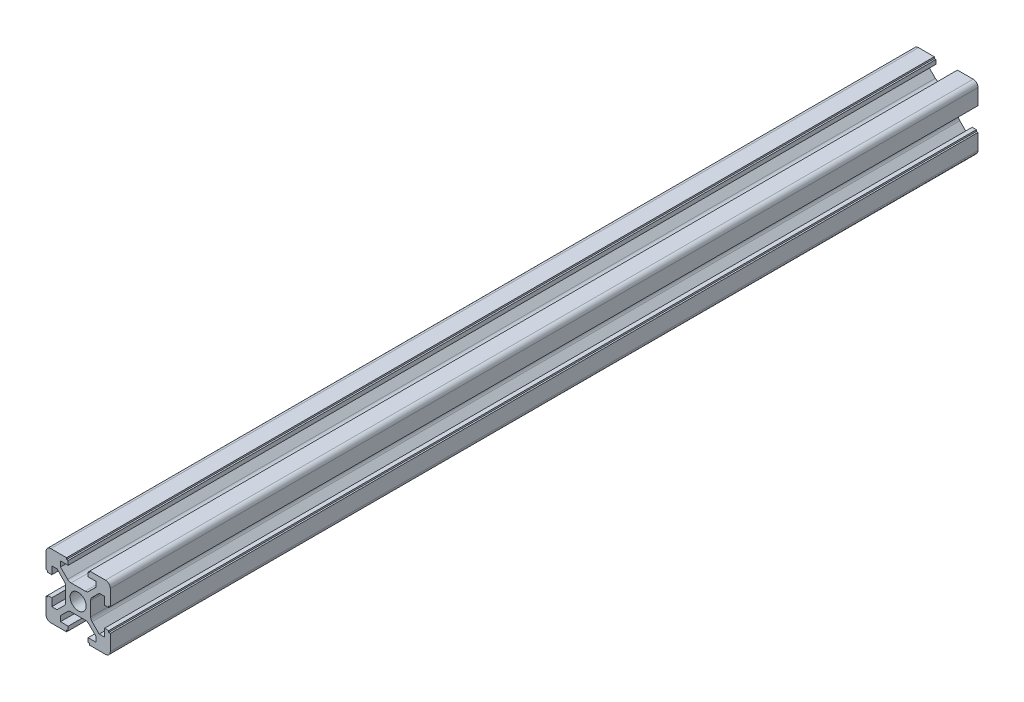
SolidWorks part; units mm, degrees
material "6061 合金"
ref_plane "前视基准面" through (0, 0, 0) normal (0, 0, 1) x (1, 0, 0)
ref_plane "上视基准面" through (0, 0, 0) normal (0, 1, 0) x (1, 0, 0)
ref_plane "右视基准面" through (0, 0, 0) normal (1, 0, 0) x (0, 0, -1)
sketch "草图1" plane through (0, 0, 0) normal (0, 0, 1) x (1, 0, 0)
  line L0 (-6.5607, 5.5) -> (-4.3393, 3.2787)
  line L1 (-3.9, 2.218) -> (-3.9, -2.218)
  line L2 (-4.3393, -3.2787) -> (-6.5607, -5.5)
  line L3 (-6.5607, -5.5) -> (-8.2, -5.5)
  line L4 (-8.2, -5.5) -> (-8.2, -3.1)
  line L5 (-8.2, -3.1) -> (-9.5, -3.1)
  line L6 (-9.5, -3.1) -> (-9.5, -3.6)
  line L7 (-9.5, -3.6) -> (-10, -3.6)
  line L8 (-10, -3.6) -> (-10, -8.5)
  line L9 (-6.5607, 5.5) -> (-8.2, 5.5)
  line L10 (-8.2, 5.5) -> (-8.2, 3.1)
  line L11 (-8.2, 3.1) -> (-9.5, 3.1)
  line L12 (-9.5, 3.1) -> (-9.5, 3.6)
  line L13 (-9.5, 3.6) -> (-10, 3.6)
  line L14 (-10, 3.6) -> (-10, 8.5)
  line L15 (5.5, 6.5607) -> (3.2787, 4.3393)
  line L16 (2.218, 3.9) -> (-2.218, 3.9)
  line L17 (-3.2787, 4.3393) -> (-5.5, 6.5607)
  line L18 (-5.5, 6.5607) -> (-5.5, 8.2)
  line L19 (-5.5, 8.2) -> (-3.1, 8.2)
  line L20 (-3.1, 8.2) -> (-3.1, 9.5)
  line L21 (-3.1, 9.5) -> (-3.6, 9.5)
  line L22 (-3.6, 9.5) -> (-3.6, 10)
  line L23 (-3.6, 10) -> (-8.5, 10)
  line L24 (5.5, 6.5607) -> (5.5, 8.2)
  line L25 (5.5, 8.2) -> (3.1, 8.2)
  line L26 (3.1, 8.2) -> (3.1, 9.5)
  line L27 (3.1, 9.5) -> (3.6, 9.5)
  line L28 (3.6, 9.5) -> (3.6, 10)
  line L29 (3.6, 10) -> (8.5, 10)
  line L30 (6.5607, -5.5) -> (4.3393, -3.2787)
  line L31 (3.9, -2.218) -> (3.9, 2.218)
  line L32 (4.3393, 3.2787) -> (6.5607, 5.5)
  line L33 (6.5607, 5.5) -> (8.2, 5.5)
  line L34 (8.2, 5.5) -> (8.2, 3.1)
  line L35 (8.2, 3.1) -> (9.5, 3.1)
  line L36 (9.5, 3.1) -> (9.5, 3.6)
  line L37 (9.5, 3.6) -> (10, 3.6)
  line L38 (10, 3.6) -> (10, 8.5)
  line L39 (6.5607, -5.5) -> (8.2, -5.5)
  line L40 (8.2, -5.5) -> (8.2, -3.1)
  line L41 (8.2, -3.1) -> (9.5, -3.1)
  line L42 (9.5, -3.1) -> (9.5, -3.6)
  line L43 (9.5, -3.6) -> (10, -3.6)
  line L44 (10, -3.6) -> (10, -8.5)
  line L45 (-5.5, -6.5607) -> (-3.2787, -4.3393)
  line L46 (-2.218, -3.9) -> (2.218, -3.9)
  line L47 (3.2787, -4.3393) -> (5.5, -6.5607)
  line L48 (5.5, -6.5607) -> (5.5, -8.2)
  line L49 (5.5, -8.2) -> (3.1, -8.2)
  line L50 (3.1, -8.2) -> (3.1, -9.5)
  line L51 (3.1, -9.5) -> (3.6, -9.5)
  line L52 (3.6, -9.5) -> (3.6, -10)
  line L53 (3.6, -10) -> (8.5, -10)
  line L54 (-5.5, -6.5607) -> (-5.5, -8.2)
  line L55 (-5.5, -8.2) -> (-3.1, -8.2)
  line L56 (-3.1, -8.2) -> (-3.1, -9.5)
  line L57 (-3.1, -9.5) -> (-3.6, -9.5)
  line L58 (-3.6, -9.5) -> (-3.6, -10)
  line L59 (-3.6, -10) -> (-8.5, -10)
  line L60 (0, 0) -> (-3.9, 2.8393) construction
  line L61 (0, 0) -> (2.8393, 3.9) construction
  arc A0 (4.3393, -3.2787) -> (3.9, -2.218) centre (5.4, -2.218) cw
  arc A1 (3.9, 2.218) -> (4.3393, 3.2787) centre (5.4, 2.218) cw
  arc A2 (3.2787, 4.3393) -> (2.218, 3.9) centre (2.218, 5.4) cw
  arc A3 (-2.218, 3.9) -> (-3.2787, 4.3393) centre (-2.218, 5.4) cw
  arc A4 (-4.3393, 3.2787) -> (-3.9, 2.218) centre (-5.4, 2.218) cw
  arc A5 (-3.9, -2.218) -> (-4.3393, -3.2787) centre (-5.4, -2.218) cw
  arc A6 (2.218, -3.9) -> (3.2787, -4.3393) centre (2.218, -5.4) cw
  arc A7 (-3.2787, -4.3393) -> (-2.218, -3.9) centre (-2.218, -5.4) cw
  arc A8 (-10, -8.5) -> (-8.5, -10) centre (-8.5, -8.5) ccw
  arc A9 (10, -8.5) -> (8.5, -10) centre (8.5, -8.5) cw
  arc A10 (8.5, 10) -> (10, 8.5) centre (8.5, 8.5) cw
  arc A11 (-10, 8.5) -> (-8.5, 10) centre (-8.5, 8.5) cw
  circle A12 centre (0, 0) radius 2.5
  point P27 (-3.9, 0)
  point P75 (2.8393, 3.9)
  dimension "D12" = 1.5
  dimension "D13" = 5
  dimension "D2" = 20
  dimension "D3" = 7.2
  dimension "D4" = 6.2
  dimension "D5" = 7.8
  dimension "D6" = 45
  dimension "D7" = 1.5
  dimension "D8" = 11
  dimension "D9" = 1.8
  dimension "D10" = 0.5
  dimension "D11" = 3.1
  dimension "D1" = 4
extrude "凸台-拉伸1" add sketch "草图1" along normal mid plane 270
sketch "草图2" plane through (0, 10, 0) normal (0, 1, 0) x (1, 0, 0)
  line L0 (2.218, 135) -> (-2.218, 135) construction
  circle A0 centre (0, 125) radius 1.6
  circle A1 centre (0, 110) radius 1.6
  circle A2 centre (0, 95) radius 1.6
  dimension "D1" = 3.2
  dimension "D2" = 10
  dimension "D3" = 15
  dimension "D4" = 15
extrude "切除-拉伸1" cut sketch "草图2" against normal through all
